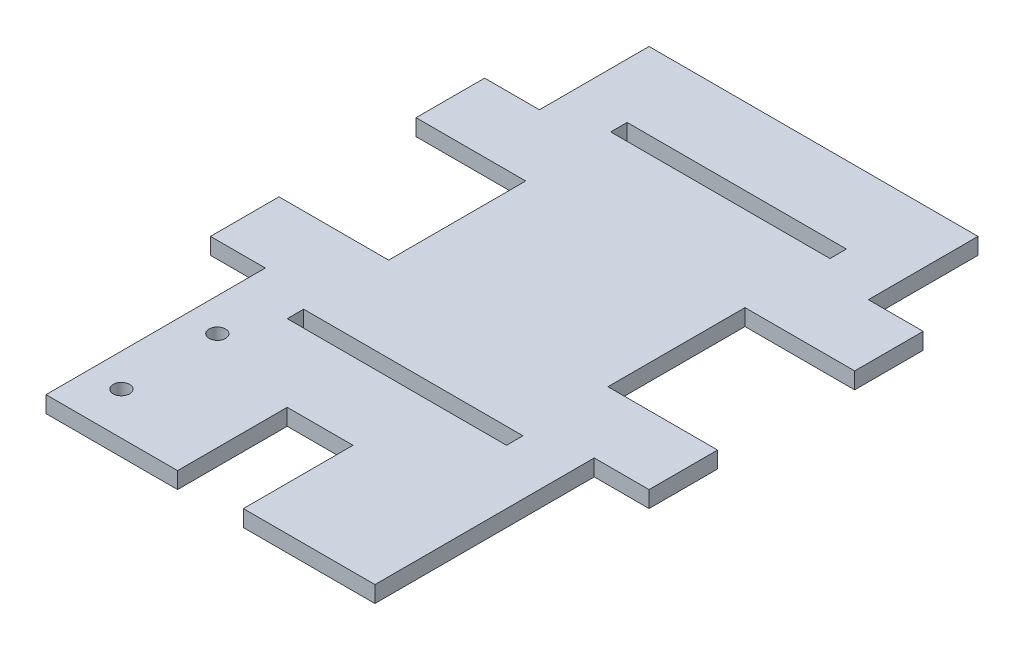
SolidWorks part; units mm, degrees
ref_plane "Front Plane" through (0, 0, 0) normal (0, 0, 1) x (1, 0, 0)
ref_plane "Top Plane" through (0, 0, 0) normal (0, 1, 0) x (1, 0, 0)
ref_plane "Right Plane" through (0, 0, 0) normal (1, 0, 0) x (0, 0, -1)
sketch "Sketch1" plane through (0, 0, 0) normal (0, 1, 0) x (1, 0, 0)
  line L0 (0, 25) -> (80, 25)
  line L1 (0, 0) -> (80, 0)
  line L2 (0, 0) -> (0, 50)
  line L3 (0, 50) -> (80, 50)
  line L4 (80, 0) -> (80, 50)
  line L5 (10, 0) -> (70, 0)
  line L6 (10, 0) -> (10, -40)
  line L7 (10, -40) -> (70, -40)
  line L8 (70, 0) -> (70, -40)
  line L9 (20, -3) -> (60, -3)
  line L10 (20, -3) -> (20, -6)
  line L11 (20, -6) -> (60, -6)
  line L12 (60, -3) -> (60, -6)
  line L13 (20, 53) -> (20, 56)
  line L14 (60, 53) -> (60, 56)
  line L15 (20, 53) -> (60, 53)
  line L16 (20, 56) -> (60, 56)
  line L17 (70, 50) -> (70, 90)
  line L18 (10, 90) -> (70, 90)
  line L19 (10, 50) -> (10, 90)
  line L20 (0, 50) -> (80, 50)
  line L21 (0, 50) -> (0, 25)
  line L22 (0, 37.5) -> (20, 37.5)
  line L23 (20, 37.5) -> (20, 12.5)
  line L24 (20, 25) -> (60, 25)
  line L25 (60, 12.5) -> (60, 37.5)
  line L26 (60, 37.5) -> (80, 37.5)
  line L27 (60, 12.5) -> (80, 12.5)
  line L28 (0, 12.5) -> (20, 12.5)
  point P13 (40, -3)
  point P14 (40, 0)
  dimension "D1" = 80
  dimension "D2" = 50
  dimension "D3" = 10
  dimension "D4" = 10
  dimension "D5" = 40
  dimension "D6" = 3
  dimension "D7" = 3
  dimension "D8" = 40
  dimension "D9" = 0
extrude "Boss-Extrude1" add sketch "Sketch1" along normal blind 3 contours L1 L4 L3 L2 | L8 L1 L6 L7 L9 L12 L11 L10 | L25 L26 L4 L3 L21 L22 L23 L0 | L19 L3 L17 L18 L13 L16 L14 L15
sketch "Sketch3" plane through (0, 0, 0) normal (0, 1, 0) x (1, 0, 0)
  line L0 (40, -40) -> (40, -6)
  line L1 (10, -40) -> (70, -40) construction
  line L2 (20, -6) -> (60, -6) construction
  line L4 (10, 0) -> (10, -40) construction
  line L6 (70, 50) -> (70, 90) construction
  line L7 (34, -40) -> (34, -20)
  line L8 (34, -20) -> (46, -20)
  line L9 (10, -32) -> (10, -40)
  line L11 (34, -40) -> (46, -40)
  line L12 (46, -40) -> (46, -20)
  line L14 (70, -32) -> (70, -40)
  line L15 (70, -40) -> (54, -40)
  line L17 (10, 90) -> (70, 90)
  line L18 (34, -13.9996) -> (34, -40)
  line L19 (26, -40) -> (34, -40)
  line L20 (26, -40) -> (34, -40)
  line L21 (54, -40) -> (46, -40)
  line L22 (10, 90) -> (10, 70)
  line L23 (10, 70) -> (70, 70)
  line L24 (70, 90) -> (70, 70)
  line L25 (10, -40) -> (16, -40)
  line L26 (16, -40) -> (16, -32.25)
  line L27 (16, -32.25) -> (16, -14.75)
  circle A0 centre (16, -32.25) radius 1.5
  circle A1 centre (16, -14.75) radius 1.5
  point P18 (40, -20)
  dimension "D7" = 3
  dimension "D8" = 3
  dimension "D1" = 6
  dimension "D2" = 6
  dimension "D3" = 7.75
  dimension "D4" = 20
  dimension "D5" = 20
  dimension "D6" = 17.5
extrude "Cut-Extrude2" cut sketch "Sketch3" along normal blind 10
